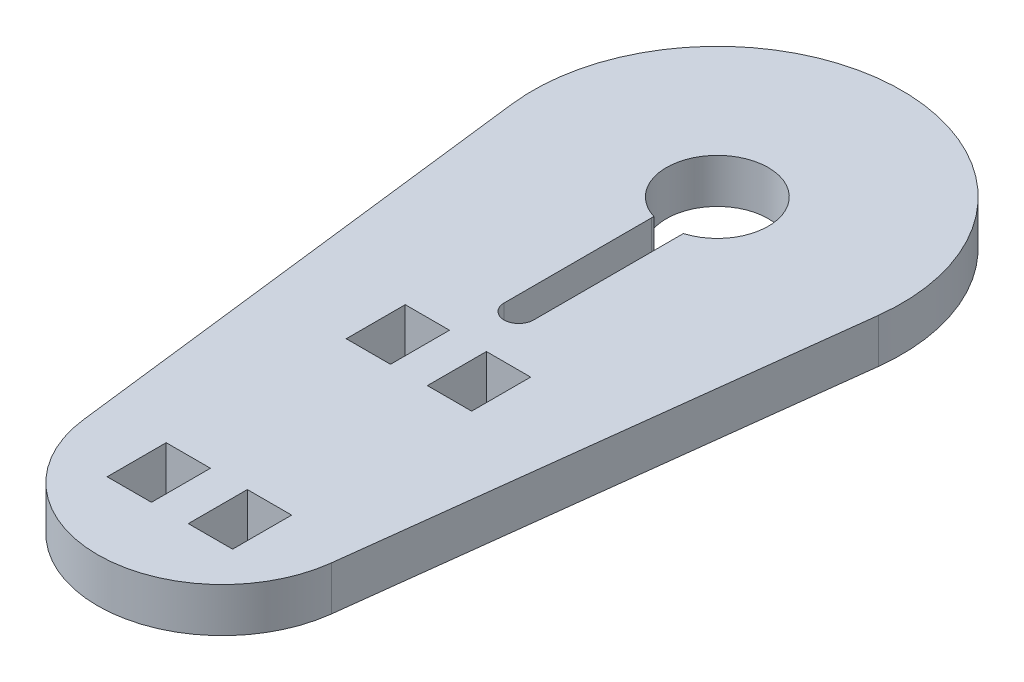
SolidWorks part; units mm, degrees
ref_plane "Front Plane" through (0, 0, 0) normal (0, 0, 1) x (1, 0, 0)
ref_plane "Top Plane" through (0, 0, 0) normal (0, 1, 0) x (1, 0, 0)
ref_plane "Right Plane" through (0, 0, 0) normal (1, 0, 0) x (0, 0, -1)
sketch "Sketch1" plane through (0, 0, 0) normal (0, 1, 0) x (1, 0, 0)
  line L0 (-7.5, -42) -> (-12.4092, -1.5043)
  line L1 (7.5, -42) -> (-7.5, -42)
  line L2 (7.5, -42) -> (7.5, -12)
  line L3 (7.5, -12) -> (-7.5, -12)
  line L4 (-7.5, -42) -> (-7.5, -12)
  line L5 (7.5, -42) -> (-7.5, -12) construction
  line L6 (7.5, -12) -> (-7.5, -42) construction
  line L7 (7.5, -42) -> (12.4092, -1.5043)
  line L8 (0, -27) -> (0, -12) construction
  line L9 (4.25, -16.9) -> (1.25, -16.9)
  line L10 (-4.25, -20.9) -> (-1.25, -20.9)
  line L11 (-4.25, -20.9) -> (-4.25, -16.9)
  line L12 (-4.25, -16.9) -> (-1.25, -16.9)
  line L13 (-1.25, -20.9) -> (-1.25, -16.9)
  line L14 (-4.25, -20.9) -> (-1.25, -16.9) construction
  line L15 (-4.25, -16.9) -> (-1.25, -20.9) construction
  line L16 (1.25, -20.9) -> (1.25, -16.9)
  line L17 (4.25, -20.9) -> (1.25, -20.9)
  line L18 (4.25, -20.9) -> (4.25, -16.9)
  line L19 (0, -27) -> (-7.5, -27) construction
  line L20 (4.25, -33.1) -> (4.25, -37.1)
  line L21 (4.25, -33.1) -> (1.25, -33.1)
  line L22 (1.25, -33.1) -> (1.25, -37.1)
  line L23 (4.25, -37.1) -> (1.25, -37.1)
  line L24 (-4.25, -37.1) -> (-1.25, -37.1)
  line L25 (-1.25, -33.1) -> (-1.25, -37.1)
  line L26 (-4.25, -33.1) -> (-1.25, -33.1)
  line L27 (-4.25, -33.1) -> (-4.25, -37.1)
  line L28 (0, -3.45) -> (0, -13.45) construction
  line L29 (1, -3.45) -> (1, -13.45)
  line L30 (-1, -3.45) -> (-1, -13.45)
  arc A0 (-1, -12.4599) -> (1, -12.4599) centre (0, 0) ccw
  circle A1 centre (0, 0) radius 3.45
  arc A4 (12.4092, -1.5043) -> (-12.4092, -1.5043) centre (0, 0) ccw
  arc A5 (1, -3.45) -> (-1, -3.45) centre (0, -3.45) ccw
  arc A6 (-1, -13.45) -> (1, -13.45) centre (0, -13.45) ccw
  point P3 (0, -27)
  point P17 (-2.75, -18.9)
  point P38 (0, -8.45)
  dimension "D2" = 6.9
  dimension "D3" = 25
  dimension "D5" = 3
  dimension "D1" = 15
  dimension "D4" = 27
  dimension "D6" = 10
  dimension "D9" = 4
  dimension "D10" = 1.25
  dimension "D11" = 6.1
  dimension "D12" = 30
  dimension "D13" = 2
extrude "Boss-Extrude2" add sketch "Sketch1" along normal blind 3
fillet "Fillet1" radius 8.4641 4 edges at (0, 0, 42) (0, 3, 42) (-7.5, 1.5, 42) (7.5, 1.5, 42)
